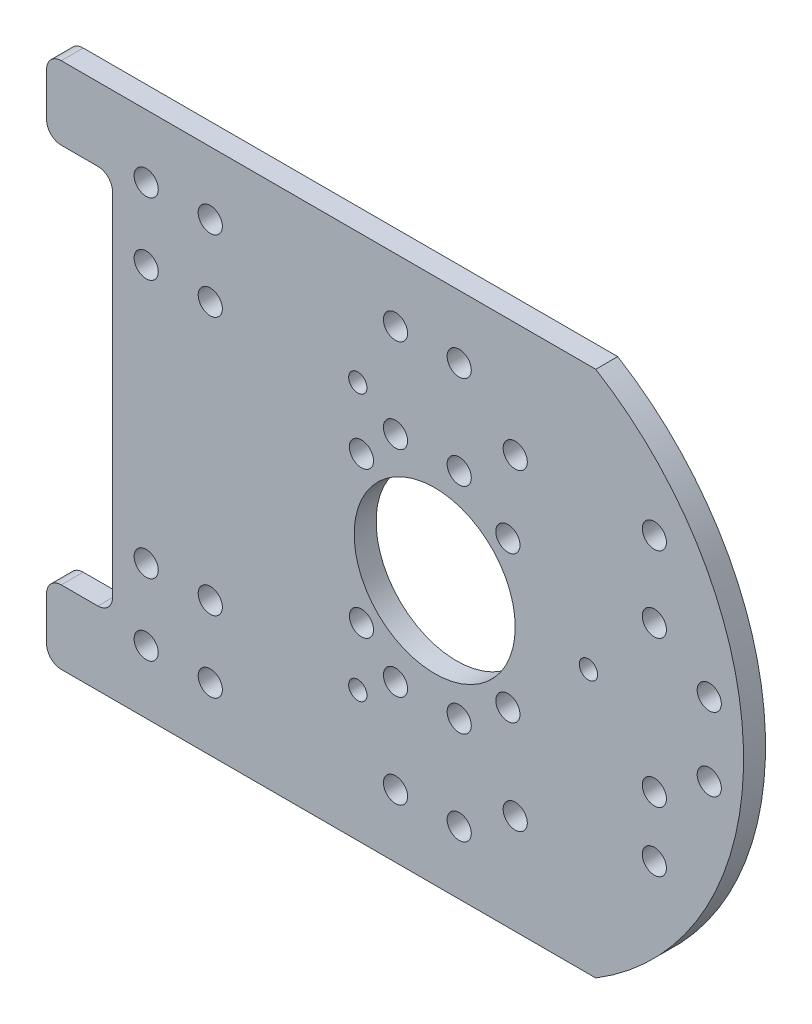
SolidWorks part; units mm, degrees
ref_plane "前视基准面" through (0, 0, 0) normal (0, 0, 1) x (1, 0, 0)
ref_plane "上视基准面" through (0, 0, 0) normal (0, 1, 0) x (1, 0, 0)
ref_plane "右视基准面" through (0, 0, 0) normal (1, 0, 0) x (0, 0, -1)
sketch "草图3" plane through (0, 0, 0) normal (0, 0, 1) x (1, 0, 0)
  line L0 (0, 0) -> (75, 0)
  line L1 (75, 0) -> (75, 72)
  line L2 (75, 72) -> (0, 72)
  line L3 (0, 72) -> (0, 0)
  line L4 (0, 69) -> (75, 69)
  line L5 (0, 3) -> (75, 3)
  line L6 (12, 3) -> (12, 0)
  line L7 (53, 36) -> (74, 36)
  line L11 (24, 3) -> (24, 0)
  line L14 (46, 3) -> (46, 0)
  line L15 (58, 3) -> (58, 0)
  line L16 (12, 69) -> (12, 72)
  line L17 (24, 69) -> (24, 72)
  line L18 (46, 69) -> (46, 72)
  line L19 (58, 69) -> (58, 72)
  line L20 (43, 46) -> (83, 46)
  line L21 (0, 62) -> (9, 62)
  line L22 (0, 62) -> (0, 10)
  line L23 (0, 10) -> (9, 10)
  line L24 (9, 62) -> (9, 10)
  line L25 (83, 36) -> (83, 46)
  line L28 (43, 26) -> (83, 26)
  line L29 (83, 36) -> (83, 26)
  line L31 (83, 36) -> (78, 31)
  line L36 (62.35, 13.65) -> (62.35, 56.35)
  line L38 (65.65, 13.65) -> (65.65, 56.35)
  circle A0 centre (13.6, 53.65) radius 1.65
  circle A1 centre (74, 36) radius 1.25
  circle A2 centre (22.35, 63.4) radius 1.65
  circle A3 centre (47.65, 63.4) radius 1.65
  circle A4 centre (43, 46) radius 1.65
  circle A5 centre (43, 26) radius 1.65
  circle A6 centre (90.5, 41) radius 1.65
  circle A7 centre (83, 56.35) radius 1.65
  circle A8 centre (13.6, 8.6) radius 1.65
  circle A9 centre (64, 56.35) radius 1.65
  circle A10 centre (56.35, 8.6) radius 1.65
  circle A11 centre (56.35, 63.4) radius 1.65
  circle A12 centre (13.6, 63.4) radius 1.65
  circle A13 centre (90.5, 31) radius 1.65
  circle A14 centre (64, 13.65) radius 1.65
  circle A15 centre (83, 17.8135) radius 1.65
  circle A16 centre (63, 46) radius 1.65
  arc A17 (75, 72) -> (75, 0) centre (53, 36) cw
  circle A18 centre (22.35, 53.65) radius 1.65
  circle A19 centre (47.65, 8.6) radius 1.65
  circle A22 centre (42.5, 54.1865) radius 1.25
  circle A23 centre (47.65, 50.65) radius 1.65
  circle A24 centre (56.35, 50.65) radius 1.65
  circle A25 centre (47.65, 21.35) radius 1.65
  circle A26 centre (22.35, 18.35) radius 1.65
  circle A27 centre (13.6, 18.35) radius 1.65
  circle A28 centre (56.35, 21.35) radius 1.65
  circle A29 centre (22.35, 8.6) radius 1.65
  circle A31 centre (42.5, 17.8135) radius 1.25
  circle A32 centre (83, 46) radius 1.65
  circle A33 centre (83, 26) radius 1.65
  circle A34 centre (63, 26) radius 1.65
  circle A35 centre (53, 36) radius 11
  dimension "D3" = 72
  dimension "D1" = 8.6
  dimension "D4" = 22
  dimension "D2" = 32
extrude "凸台-拉伸2" add sketch "草图3" along normal blind 3
fillet "圆角2" radius 2 6 edges at (0, 0, 1.5) (0, 10, 1.5) (9, 10, 1.5) (9, 62, 1.5) (0, 62, 1.5) (0, 72, 1.5)
